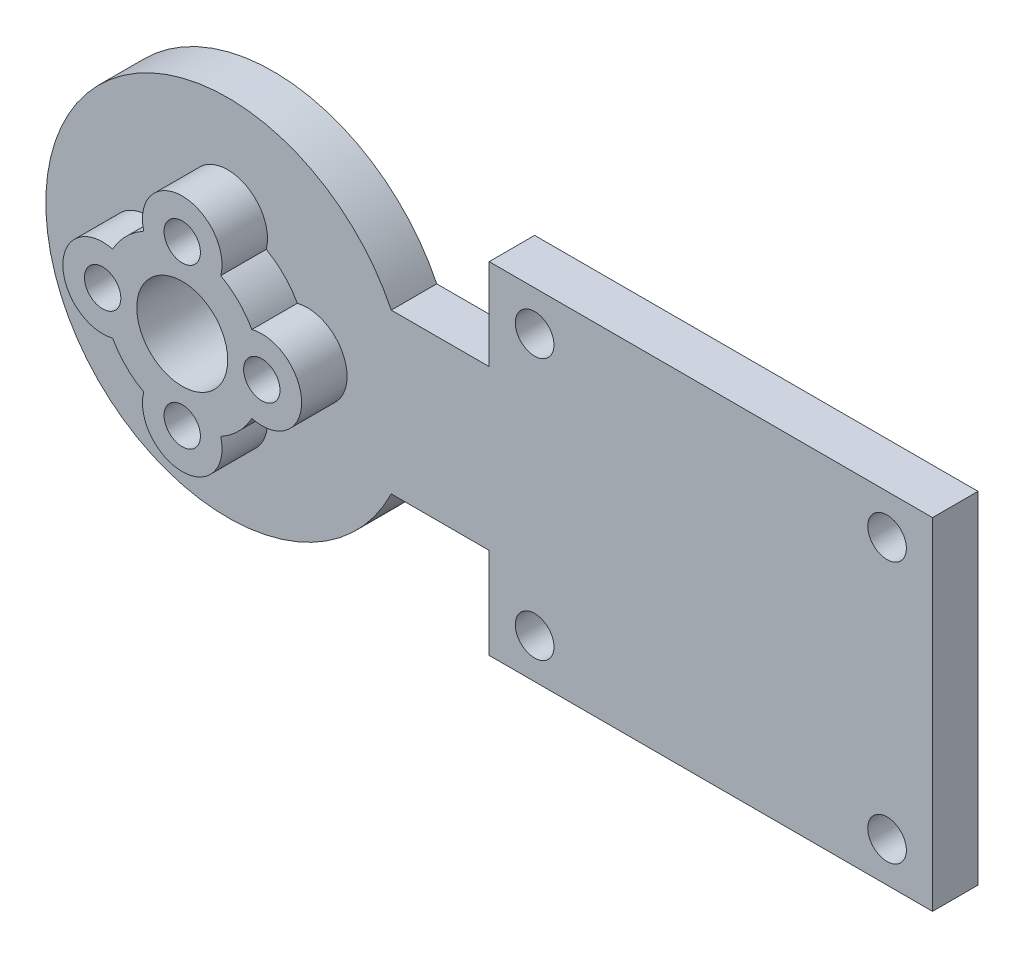
SolidWorks part; units mm, degrees
ref_plane "Front Plane" through (0, 0, 0) normal (0, 0, 1) x (1, 0, 0)
ref_plane "Top Plane" through (0, 0, 0) normal (0, 1, 0) x (1, 0, 0)
ref_plane "Right Plane" through (0, 0, 0) normal (1, 0, 0) x (0, 0, -1)
sketch "Metal_horn_flange_profile" plane through (0, 0, 0) normal (0, 0, 1) x (1, 0, 0)
  circle A0 centre (0, 0) radius 16
  dimension "D1" = 32
extrude "Metal_horn_flange" add sketch "Metal_horn_flange_profile" along normal blind 4
sketch "Straight_forearm_web_profile" plane through (0, 0, 0) normal (0, 0, 1) x (1, 0, 0)
  line L1 (0, -7) -> (28, -7)
  line L2 (0, -7) -> (0, 7)
  line L3 (0, 7) -> (28, 7)
  line L4 (28, -7) -> (28, 7)
  dimension "D1" = 28
  dimension "D2" = 14
extrude "Straight_forearm_web" add sketch "Straight_forearm_web_profile" along normal blind 4
sketch "Replaceable_tool_mounting_deck_profile" plane through (0, 0, 0) normal (0, 0, 1) x (1, 0, 0)
  line L1 (23, -15) -> (62, -15)
  line L2 (23, -15) -> (23, 15)
  line L3 (23, 15) -> (62, 15)
  line L4 (62, -15) -> (62, 15)
  dimension "D1" = 39
  dimension "D2" = 30
extrude "Replaceable_tool_mounting_deck" add sketch "Replaceable_tool_mounting_deck_profile" along normal blind 4
sketch "Dowel_support_hub_profile" plane through (0, 0, 0) normal (0, 0, 1) x (1, 0, 0)
  circle A0 centre (0, 0) radius 7
  circle A1 centre (0, 0) radius 4
  dimension "D1" = 14
  dimension "D2" = 8
extrude "Dowel_support_hub" add sketch "Dowel_support_hub_profile" along normal blind 4 from offset 4
sketch "Raised_washer_seats_PCD14" plane through (0, 0, 0) normal (0, 0, 1) x (1, 0, 0)
  circle A0 centre (7, 0) radius 3.5
  circle A1 centre (-7, 0) radius 3.5
  circle A2 centre (0, 7) radius 3.5
  circle A3 centre (0, -7) radius 3.5
  dimension "D1" = 7
  dimension "D2" = 7
  dimension "D3" = 7
  dimension "D4" = 7
extrude "Washer_seats_clear_dowel_sleeve" add sketch "Raised_washer_seats_PCD14" along normal blind 4 from offset 4
sketch "Metal_horn_M3_pattern_profile" plane through (0, 0, 0) normal (0, 0, 1) x (1, 0, 0)
  circle A0 centre (7, 0) radius 1.6
  circle A1 centre (-7, 0) radius 1.6
  circle A2 centre (0, 7) radius 1.6
  circle A3 centre (0, -7) radius 1.6
  dimension "D1" = 3.2
  dimension "D2" = 3.2
  dimension "D3" = 3.2
  dimension "D4" = 3.2
extrude "Metal_horn_M3_pattern" cut sketch "Metal_horn_M3_pattern_profile" along normal through all from offset 50
sketch "Elbow_sleeve_bore_profile" plane through (0, 0, 0) normal (0, 0, 1) x (1, 0, 0)
  circle A0 centre (0, 0) radius 4
  dimension "D1" = 8
extrude "Elbow_sleeve_bore" cut sketch "Elbow_sleeve_bore_profile" along normal through all from offset 50
sketch "Modular_tool_four_M3_pattern_profile" plane through (0, 0, 0) normal (0, 0, 1) x (1, 0, 0)
  circle A0 centre (27, -11.5) radius 1.7
  circle A1 centre (27, 11.5) radius 1.7
  circle A2 centre (58, -11.5) radius 1.7
  circle A3 centre (58, 11.5) radius 1.7
  dimension "D1" = 3.4
  dimension "D2" = 3.4
  dimension "D3" = 3.4
  dimension "D4" = 3.4
extrude "Modular_tool_four_M3_pattern" cut sketch "Modular_tool_four_M3_pattern_profile" along normal through all from offset 50
